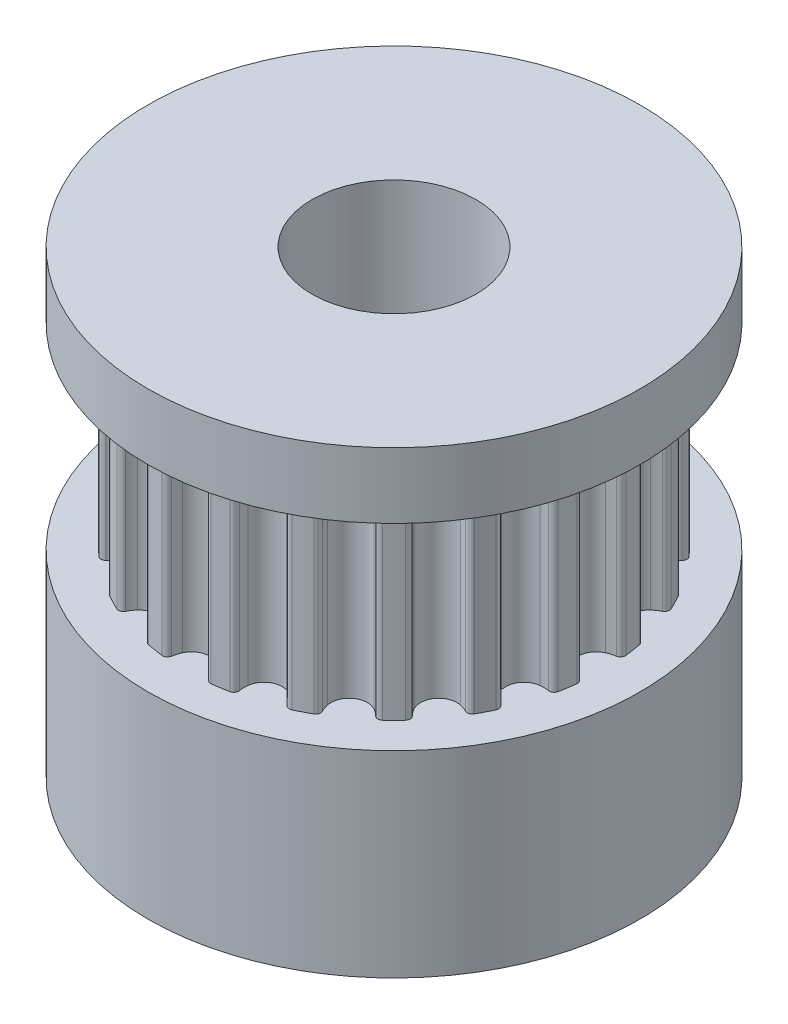
SolidWorks part; units mm, degrees
ref_plane "Front Plane" through (0, 0, 0) normal (0, 0, 1) x (1, 0, 0)
ref_plane "Top Plane" through (0, 0, 0) normal (0, 1, 0) x (1, 0, 0)
ref_plane "Right Plane" through (0, 0, 0) normal (1, 0, 0) x (0, 0, -1)
sketch "Sketch1" plane through (0, 0, 0) normal (0, 1, 0) x (1, 0, 0)
  arc A0 (-3.4095, 7.061) -> (-1.9125, 7.061) centre (-2.661, 0.7392) ccw
  arc A1 (-2.1539, 6.6821) -> (-2.0783, 6.9356) centre (-3.0659, 7.0923) ccw
  arc A2 (-3.1681, 6.6821) -> (-2.1539, 6.6821) centre (-2.661, 6.9102) ccw
  arc A3 (-3.2437, 6.9356) -> (-3.1681, 6.6821) centre (-2.2561, 7.0923) ccw
  arc A4 (-1.9125, 7.061) -> (-2.0783, 6.9356) centre (-1.9301, 6.9121) ccw
  arc A5 (-3.4095, 7.061) -> (-3.2437, 6.9356) centre (-3.3919, 6.9121) cw
  arc A6 (-1.4193, 6.9829) -> (-1.3004, 6.8124) centre (-1.4486, 6.8358) cw
  arc A7 (-1.3004, 6.8124) -> (-1.3068, 6.5479) centre (-0.3127, 6.6562) ccw
  arc A8 (-1.3068, 6.5479) -> (-0.3423, 6.2346) centre (-0.7541, 6.6081) ccw
  arc A9 (-0.3423, 6.2346) -> (-0.192, 6.4522) centre (-1.0829, 6.9065) ccw
  arc A10 (0.0044, 6.5203) -> (-0.192, 6.4522) centre (-0.0584, 6.3841) ccw
  arc A11 (0.4493, 6.2936) -> (0.5097, 6.0947) centre (0.3761, 6.1627) cw
  arc A12 (0.5097, 6.0947) -> (0.4219, 5.8452) centre (1.4009, 5.6409) ccw
  arc A13 (0.4219, 5.8452) -> (1.2424, 5.2491) centre (0.9662, 5.7316) ccw
  arc A14 (1.2424, 5.2491) -> (1.4526, 5.4096) centre (0.7457, 6.117) ccw
  arc A15 (1.6604, 5.4137) -> (1.4526, 5.4096) centre (1.5586, 5.3036) ccw
  arc A16 (2.0135, 5.0606) -> (2.0095, 4.8527) centre (1.9034, 4.9588) cw
  arc A17 (2.0095, 4.8527) -> (1.8489, 4.6426) centre (2.7168, 4.1458) ccw
  arc A18 (1.8489, 4.6426) -> (2.445, 3.8221) centre (2.3314, 4.3664) ccw
  arc A19 (2.445, 3.8221) -> (2.6945, 3.9099) centre (2.2408, 4.801) ccw
  arc A20 (2.8934, 3.8495) -> (2.6945, 3.9099) centre (2.7626, 3.7762) ccw
  arc A21 (3.1201, 3.4046) -> (3.052, 3.2081) centre (2.9839, 3.3418) cw
  arc A22 (3.052, 3.2081) -> (2.8344, 3.0579) centre (3.5063, 2.3173) ccw
  arc A23 (2.8344, 3.0579) -> (3.1478, 2.0934) centre (3.208, 2.6461) ccw
  arc A24 (3.1478, 2.0934) -> (3.4122, 2.0998) centre (3.256, 3.0875) ccw
  arc A25 (3.5827, 1.9809) -> (3.4122, 2.0998) centre (3.4356, 1.9516) ccw
  arc A26 (3.6608, 1.4877) -> (3.5354, 1.3219) centre (3.5119, 1.47) cw
  arc A27 (3.5354, 1.3219) -> (3.282, 1.2462) centre (3.6921, 0.3342) ccw
  arc A28 (3.282, 1.2462) -> (3.282, 0.2321) centre (3.51, 0.7392) ccw
  arc A29 (3.282, 0.2321) -> (3.5354, 0.1565) centre (3.6921, 1.1441) ccw
  arc A30 (3.6608, -0.0093) -> (3.5354, 0.1565) centre (3.5119, 0.0083) ccw
  arc A31 (3.5827, -0.5025) -> (3.4122, -0.6214) centre (3.4356, -0.4733) cw
  arc A32 (3.4122, -0.6214) -> (3.1478, -0.615) centre (3.256, -1.6092) ccw
  arc A33 (3.1478, -0.615) -> (2.8344, -1.5796) centre (3.208, -1.1678) ccw
  arc A34 (2.8344, -1.5796) -> (3.052, -1.7298) centre (3.5063, -0.8389) ccw
  arc A35 (3.1201, -1.9262) -> (3.052, -1.7298) centre (2.9839, -1.8634) ccw
  arc A36 (2.8934, -2.3712) -> (2.6945, -2.4316) centre (2.7626, -2.2979) cw
  arc A37 (2.6945, -2.4316) -> (2.445, -2.3438) centre (2.2408, -3.3227) ccw
  arc A38 (2.445, -2.3438) -> (1.8489, -3.1643) centre (2.3314, -2.8881) ccw
  arc A39 (1.8489, -3.1643) -> (2.0095, -3.3744) centre (2.7168, -2.6675) ccw
  arc A40 (2.0135, -3.5823) -> (2.0095, -3.3744) centre (1.9034, -3.4804) ccw
  arc A41 (1.6604, -3.9354) -> (1.4526, -3.9313) centre (1.5586, -3.8252) cw
  arc A42 (1.4526, -3.9313) -> (1.2424, -3.7707) centre (0.7457, -4.6386) ccw
  arc A43 (1.2424, -3.7707) -> (0.4219, -4.3668) centre (0.9662, -4.2533) ccw
  arc A44 (0.4219, -4.3668) -> (0.5097, -4.6163) centre (1.4009, -4.1626) ccw
  arc A45 (0.4493, -4.8153) -> (0.5097, -4.6163) centre (0.3761, -4.6844) ccw
  arc A46 (0.0044, -5.042) -> (-0.192, -4.9739) centre (-0.0584, -4.9057) cw
  arc A47 (-0.192, -4.9739) -> (-0.3423, -4.7562) centre (-1.0829, -5.4281) ccw
  arc A48 (-0.3423, -4.7562) -> (-1.3068, -5.0696) centre (-0.7541, -5.1298) ccw
  arc A49 (-1.3068, -5.0696) -> (-1.3004, -5.334) centre (-0.3127, -5.1779) ccw
  arc A50 (-1.4193, -5.5046) -> (-1.3004, -5.334) centre (-1.4486, -5.3574) ccw
  arc A51 (-1.9125, -5.5827) -> (-2.0783, -5.4572) centre (-1.9301, -5.4337) cw
  arc A52 (-2.0783, -5.4572) -> (-2.1539, -5.2038) centre (-3.0659, -5.6139) ccw
  arc A53 (-2.1539, -5.2038) -> (-3.1681, -5.2038) centre (-2.661, -5.4318) ccw
  arc A54 (-3.1681, -5.2038) -> (-3.2437, -5.4572) centre (-2.2561, -5.6139) ccw
  arc A55 (-3.4095, -5.5827) -> (-3.2437, -5.4572) centre (-3.3919, -5.4337) ccw
  arc A56 (-3.9027, -5.5046) -> (-4.0216, -5.334) centre (-3.8734, -5.3574) cw
  arc A57 (-4.0216, -5.334) -> (-4.0152, -5.0696) centre (-5.0093, -5.1779) ccw
  arc A58 (-4.0152, -5.0696) -> (-4.9797, -4.7562) centre (-4.5679, -5.1298) ccw
  arc A59 (-4.9797, -4.7562) -> (-5.13, -4.9739) centre (-4.2391, -5.4281) ccw
  arc A60 (-5.3264, -5.042) -> (-5.13, -4.9739) centre (-5.2636, -4.9057) ccw
  arc A61 (-5.7713, -4.8153) -> (-5.8317, -4.6163) centre (-5.6981, -4.6844) cw
  arc A62 (-5.8317, -4.6163) -> (-5.7439, -4.3668) centre (-6.7229, -4.1626) ccw
  arc A63 (-5.7439, -4.3668) -> (-6.5644, -3.7707) centre (-6.2882, -4.2533) ccw
  arc A64 (-6.5644, -3.7707) -> (-6.7746, -3.9313) centre (-6.0677, -4.6386) ccw
  arc A65 (-6.9824, -3.9354) -> (-6.7746, -3.9313) centre (-6.8806, -3.8252) ccw
  arc A66 (-7.3355, -3.5823) -> (-7.3315, -3.3744) centre (-7.2254, -3.4804) cw
  arc A67 (-7.3315, -3.3744) -> (-7.1709, -3.1643) centre (-8.0388, -2.6675) ccw
  arc A68 (-7.1709, -3.1643) -> (-7.767, -2.3438) centre (-7.6534, -2.8881) ccw
  arc A69 (-7.767, -2.3438) -> (-8.0165, -2.4316) centre (-7.5628, -3.3227) ccw
  arc A70 (-8.2154, -2.3712) -> (-8.0165, -2.4316) centre (-8.0846, -2.2979) ccw
  arc A71 (-8.4421, -1.9262) -> (-8.3741, -1.7298) centre (-8.3059, -1.8634) cw
  arc A72 (-8.3741, -1.7298) -> (-8.1564, -1.5796) centre (-8.8283, -0.8389) ccw
  arc A73 (-8.1564, -1.5796) -> (-8.4698, -0.615) centre (-8.53, -1.1678) ccw
  arc A74 (-8.4698, -0.615) -> (-8.7342, -0.6214) centre (-8.578, -1.6092) ccw
  arc A75 (-8.9047, -0.5025) -> (-8.7342, -0.6214) centre (-8.7576, -0.4733) ccw
  arc A76 (-8.9828, -0.0093) -> (-8.8574, 0.1565) centre (-8.8339, 0.0083) cw
  arc A77 (-8.8574, 0.1565) -> (-8.604, 0.2321) centre (-9.0141, 1.1441) ccw
  arc A78 (-8.604, 0.2321) -> (-8.604, 1.2462) centre (-8.832, 0.7392) ccw
  arc A79 (-8.604, 1.2462) -> (-8.8574, 1.3219) centre (-9.0141, 0.3342) ccw
  arc A80 (-8.9828, 1.4877) -> (-8.8574, 1.3219) centre (-8.8339, 1.47) ccw
  arc A81 (-8.9047, 1.9809) -> (-8.7342, 2.0998) centre (-8.7576, 1.9516) cw
  arc A82 (-8.7342, 2.0998) -> (-8.4698, 2.0934) centre (-8.578, 3.0875) ccw
  arc A83 (-8.4698, 2.0934) -> (-8.1564, 3.0579) centre (-8.53, 2.6461) ccw
  arc A84 (-8.1564, 3.0579) -> (-8.3741, 3.2081) centre (-8.8283, 2.3173) ccw
  arc A85 (-8.4421, 3.4046) -> (-8.3741, 3.2081) centre (-8.3059, 3.3418) ccw
  arc A86 (-8.2154, 3.8495) -> (-8.0165, 3.9099) centre (-8.0846, 3.7762) cw
  arc A87 (-8.0165, 3.9099) -> (-7.767, 3.8221) centre (-7.5628, 4.801) ccw
  arc A88 (-7.767, 3.8221) -> (-7.1709, 4.6426) centre (-7.6534, 4.3664) ccw
  arc A89 (-7.1709, 4.6426) -> (-7.3315, 4.8527) centre (-8.0388, 4.1458) ccw
  arc A90 (-7.3355, 5.0606) -> (-7.3315, 4.8527) centre (-7.2254, 4.9588) ccw
  arc A91 (-6.9824, 5.4137) -> (-6.7746, 5.4096) centre (-6.8806, 5.3036) cw
  arc A92 (-6.7746, 5.4096) -> (-6.5644, 5.2491) centre (-6.0677, 6.117) ccw
  arc A93 (-6.5644, 5.2491) -> (-5.7439, 5.8452) centre (-6.2882, 5.7316) ccw
  arc A94 (-5.7439, 5.8452) -> (-5.8317, 6.0947) centre (-6.7229, 5.6409) ccw
  arc A95 (-5.7713, 6.2936) -> (-5.8317, 6.0947) centre (-5.6981, 6.1627) ccw
  arc A96 (-5.3264, 6.5203) -> (-5.13, 6.4522) centre (-5.2636, 6.3841) cw
  arc A97 (-5.13, 6.4522) -> (-4.9797, 6.2346) centre (-4.2391, 6.9065) ccw
  arc A98 (-4.9797, 6.2346) -> (-4.0152, 6.5479) centre (-4.5679, 6.6081) ccw
  arc A99 (-4.0152, 6.5479) -> (-4.0216, 6.8124) centre (-5.0093, 6.6562) ccw
  arc A100 (-3.9027, 6.9829) -> (-4.0216, 6.8124) centre (-3.8734, 6.8358) ccw
  circle A101 centre (-2.661, 0.7392) radius 2.5
  point P4 (-2.661, 7.1052)
  point P223 (-2.661, 0.7392)
  point P224 (0, 0)
  dimension "D1" = 12.732
  dimension "D3" = 2
  dimension "D4" = 0.15
  dimension "D5" = 5
  dimension "D2" = 0.195
extrude "Boss-Extrude1" add sketch "Sketch1" along normal blind 10 contours A0 A100 A99 A98 A97 A96 A95 A94 A93 A92 A91 A90 A89 A88 A87 A86 A85 A84 A83 A82 A81 A80 A79 A78 A77 A76 A75 A74 A73 A72 A71 A70 A69 A68 A67 A66 A65 A64 A63 A62 A61 A60 A59
sketch "Sketch3" plane through (0, 10, 0) normal (0, 1, 0) x (1, 0, 0)
  circle A0 centre (-2.661, 0.7392) radius 7.5
  circle A1 centre (-2.661, 0.7392) radius 2.5
  circle A2 centre (-2.661, 0.7392) radius 2.5 construction
  dimension "D1" = 15
  dimension "D2" = 5
extrude "Boss-Extrude2" add sketch "Sketch3" along normal mid plane 2
sketch "Sketch4" plane through (0, 0, 0) normal (0, -1, 0) x (1, 0, 0)
  circle A0 centre (-2.661, -0.7392) radius 7.5
  circle A1 centre (-2.661, -0.7392) radius 2.5
  circle A2 centre (-2.661, -0.7392) radius 2.5 construction
  dimension "D1" = 15
  dimension "D2" = 5
extrude "Boss-Extrude3" add sketch "Sketch4" along normal blind 3 and the other way blind 3
